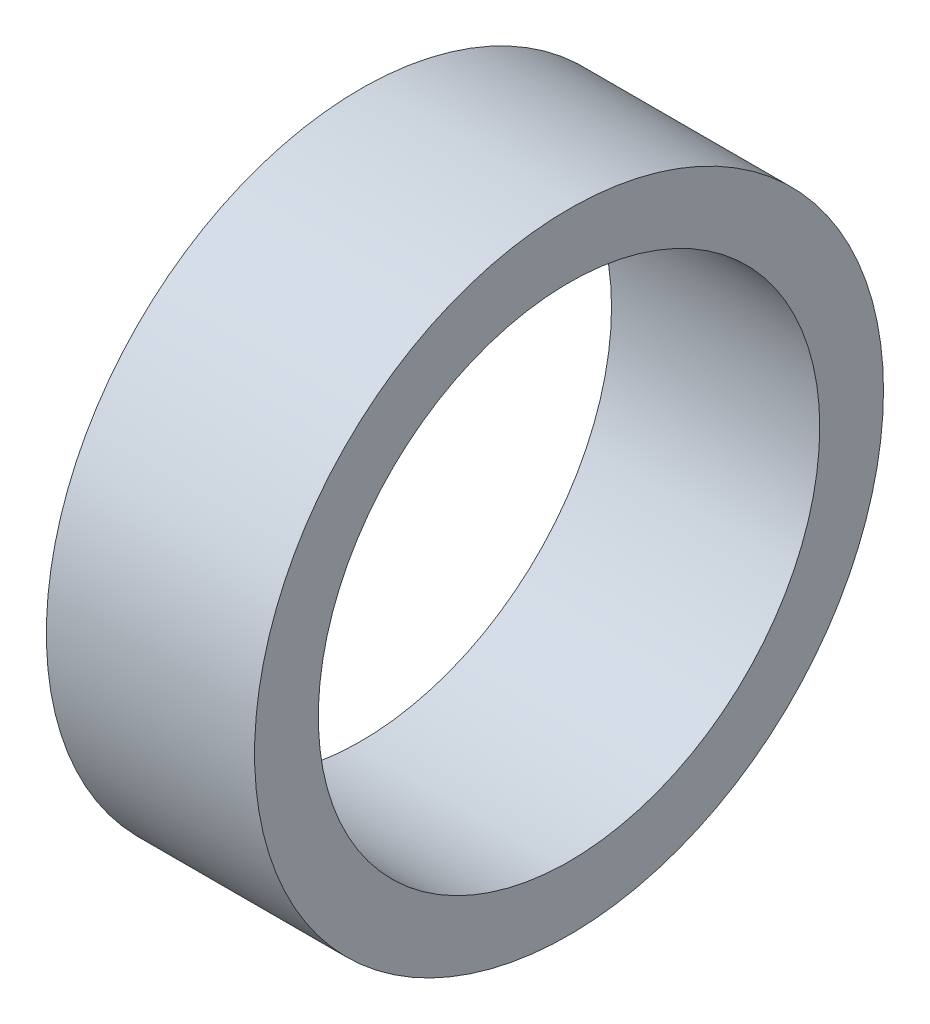
SolidWorks part; units mm, degrees
material "TPU 95A"
ref_plane "Front Plane" through (0, 0, 0) normal (1, 0, 0) x (0, 1, 0)
ref_plane "Top Plane" through (0, 0, 0) normal (0, 0, 1) x (0, 1, 0)
ref_plane "Right Plane" through (0, 0, 0) normal (0, 1, 0) x (-1, 0, 0)
sketch "Sketch1" plane through (0, 0, 0) normal (1, 0, 0) x (0, 1, 0)
  circle A0 centre (0, 0) radius 2.9972
  circle A1 centre (0, 0) radius 3.7592
  dimension "D1" = 5.9944
  dimension "D2" = 7.5184
extrude "Boss-Extrude1" add sketch "Sketch1" along normal blind 2.4892
equation "\"bore\"= 6mm"
equation "\"thickness\"= 0.03"
equation "\"D1@Sketch1\"=\"bore\""
equation "\"D2@Sketch1\"=\"bore\"+2*\"thickness\""
equation "\"D1@Boss-Extrude1\"=2.5mm"
